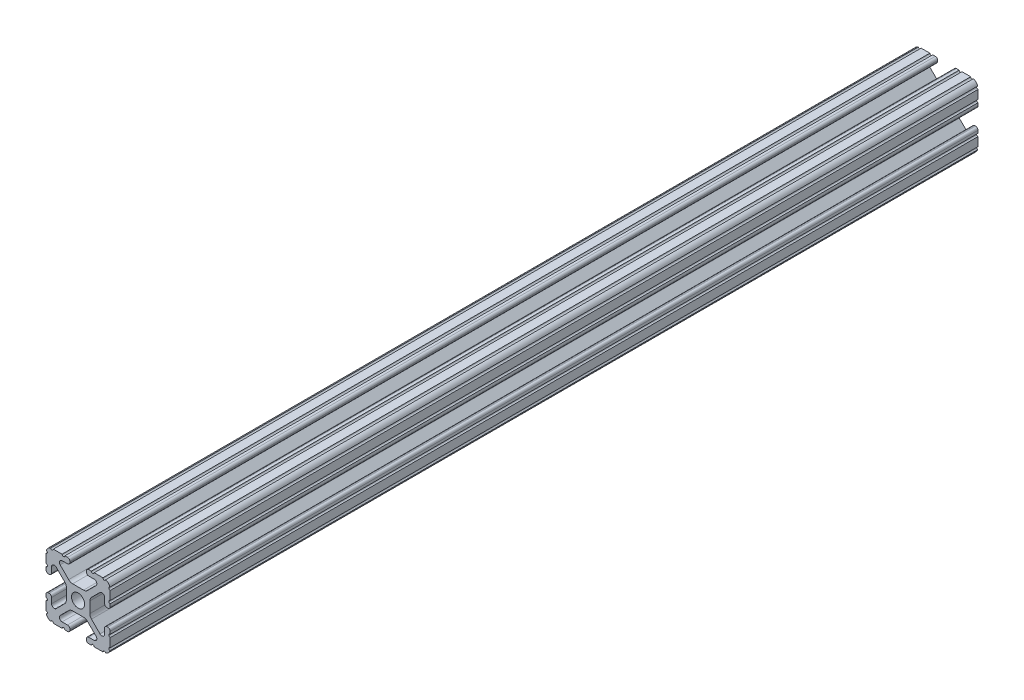
SolidWorks part; units mm, degrees
ref_plane "Front Plane" through (0, 0, 0) normal (0, 0, 1) x (1, 0, 0)
ref_plane "Top Plane" through (0, 0, 0) normal (0, 1, 0) x (1, 0, 0)
ref_plane "Right Plane" through (0, 0, 0) normal (1, 0, 0) x (0, 0, -1)
sketch "Sketch2" plane through (0, 0, 0) normal (0, 0, 1) x (1, 0, 0)
  line L0 (0, 12.7) -> (0, -12.7) construction
  line L1 (-12.7, 0) -> (12.7, 0) construction
  line L2 (3.2512, -12.7) -> (12.7, -12.7)
  line L3 (12.7, -12.7) -> (12.7, -3.2512)
  line L4 (3.2512, -12.7) -> (3.2512, -10.4902)
  line L5 (3.2512, -10.4902) -> (8.9276, -10.4902)
  line L6 (8.9276, -10.4902) -> (3.0856, -4.6482)
  line L7 (0, 0) -> (12.7, -12.7) construction
  line L8 (12.7, -3.2512) -> (10.4902, -3.2512)
  line L9 (10.4902, -3.2512) -> (10.4902, -8.9276)
  line L10 (10.4902, -8.9276) -> (4.6482, -3.0856)
  circle A0 centre (0, 0) radius 2.6035
  arc A1 (6.3485, -10.4902) -> (7.1039, -8.6665) centre (6.3485, -9.4219) ccw construction
  point P8 (0, -4.6482)
  dimension "Center Hole Diameter" = 5.207
  dimension "Rail Height" = 25.4
  dimension "Rail Width" = 25.4
  dimension "T-Slot Width" = 6.5024
  dimension "Slot Inner Width" = 14.8336
  dimension "Thickness" = 2.2098
  dimension "Slot Depth" = 5.842
  dimension "D1" = 2.2098
sketch "Sketch3" plane through (0, 0, 0) normal (1, 0, 0) x (0, 0, -1)
  line L0 (-171.6997, -12.7) -> (171.6997, -12.7) construction
  line L1 (-146.2997, 0) -> (146.2997, 0) construction
  line L3 (-171.6997, 0) -> (171.6997, 0) construction
sketch "Sketch4" plane through (0, 0, 0) normal (0, 0, 1) x (1, 0, 0)
  line L0 (4.1904, -12.7) -> (10.1173, -12.7)
  line L1 (3.2512, -12.7) -> (12.7, -12.7) construction
  line L2 (3.2512, -12.7) -> (3.2512, -10.4902) construction
  line L3 (3.2512, -10.4902) -> (8.9276, -10.4902) construction
  line L4 (3.2512, -11.4294) -> (3.2512, -11.7608)
  line L5 (4.1904, -10.4902) -> (6.3485, -10.4902)
  line L6 (0, -4.6482) -> (2.164, -4.6482)
  line L7 (8.9276, -10.4902) -> (3.0856, -4.6482) construction
  line L8 (3.7373, -5.2999) -> (7.1039, -8.6665)
  line L9 (12.7, -12.7) -> (12.7, -3.2512) construction
  line L10 (10.4902, -8.9276) -> (4.6482, -3.0856) construction
  line L11 (10.4902, -3.2512) -> (10.4902, -8.9276) construction
  line L12 (10.4902, -6.3485) -> (10.4902, -4.1904)
  line L13 (12.7, -3.2512) -> (10.4902, -3.2512) construction
  line L14 (11.4294, -3.2512) -> (11.7608, -3.2512)
  line L15 (12.7, -4.1904) -> (12.7, -10.1173)
  line L16 (8.6665, -7.1039) -> (5.2999, -3.7373)
  line L17 (4.6482, 0) -> (4.6482, -2.164)
  line L18 (-12.7, 0) -> (12.7, 0) construction
  line L19 (0, -4.6482) -> (0, -2.6035)
  line L20 (0, 12.7) -> (0, -12.7) construction
  line L21 (4.6482, 0) -> (2.6035, 0)
  arc A0 (3.2512, -11.7608) -> (4.1904, -12.7) centre (4.1904, -11.7608) ccw
  arc A2 (3.2512, -11.4294) -> (4.1904, -10.4902) centre (4.1904, -11.4294) cw
  arc A3 (6.3485, -10.4902) -> (7.1039, -8.6665) centre (6.3485, -9.4219) ccw
  arc A4 (2.164, -4.6482) -> (3.7373, -5.2999) centre (2.164, -6.8732) cw
  arc A5 (10.1173, -12.7) -> (12.7, -10.1173) centre (10.1173, -10.1173) ccw
  arc A6 (8.6665, -7.1039) -> (10.4902, -6.3485) centre (9.4219, -6.3485) ccw
  arc A7 (10.4902, -4.1904) -> (11.4294, -3.2512) centre (11.4294, -4.1904) cw
  arc A8 (11.7608, -3.2512) -> (12.7, -4.1904) centre (11.7608, -4.1904) cw
  arc A9 (5.2999, -3.7373) -> (4.6482, -2.164) centre (6.8732, -2.164) cw
  circle A10 centre (0, 0) radius 2.6035 construction
  arc A11 (0, -2.6035) -> (2.6035, 0) centre (0, 0) ccw
  dimension "D1" = 2.5827
  dimension "D2" = 2.225
  dimension "D3" = 0.9392
extrude "Boss-Extrude1" add sketch "Sketch4" along normal up to vertex (171.6997 mm away) from vertex at -171.6997 starting at point (0, -12.7, -171.6997)
sketch "Sketch5" plane through (0, 0, 0) normal (0, 0, 1) x (1, 0, 0)
  line L0 (3.2512, -12.7) -> (12.7, -12.7) construction
  line L1 (4.1904, -10.4902) -> (6.3485, -10.4902) construction
  line L3 (0, 0) -> (12.7, -12.7) construction
  line L4 (6.3485, -10.4902) -> (6.3485, -12.7) construction
  line L5 (8.9276, -10.4902) -> (3.0856, -4.6482) construction
  circle A0 centre (10.3562, -12.7) radius 0.5524
  circle A1 centre (5.796, -12.7) radius 0.5524
  circle A2 centre (12.7, -10.3562) radius 0.5524
  circle A3 centre (12.7, -5.796) radius 0.5524
  point P10 (5.2694, -10.4902)
  point P12 (9.4219, -6.3485)
  dimension "D1" = 1.1049
extrude "Cut-Extrude1" cut sketch "Sketch5" against normal through all both and the other way through all
mirror "Mirror1" about plane through (0, 0, 0) normal (1, 0, 0) of bodies 137 134
mirror "Mirror2" about plane through (0, 0, 0) normal (0, 1, 0) of bodies 135
equation "\"D1@Sketch2\"=\"Thickness@Sketch2\""
equation "\"D2@Sketch4\"=\"Slot Inner Width@Sketch2\"*0.15"
equation "\"D1@Sketch4\"=\"D3@Sketch4\"*2.75"
equation "\"D3@Sketch4\"=\"Thickness@Sketch2\"*0.425"
equation "\"D1@Sketch5\"=\"Thickness@Sketch2\"*0.5"
equation "\"D1@Boss-Extrude1\"=\"Length@Sketch3\""
